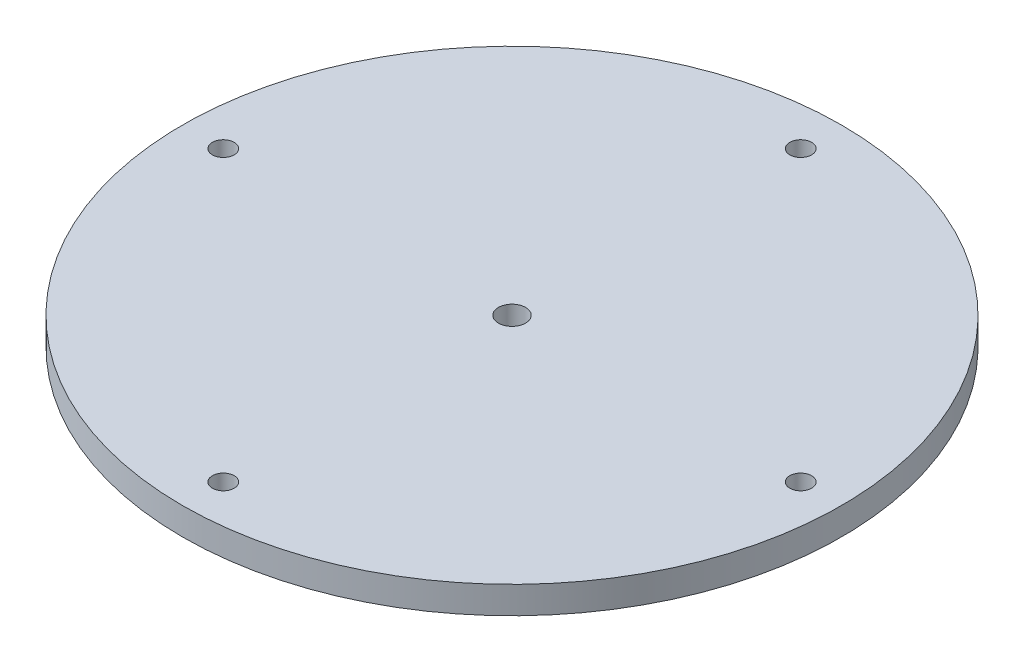
SolidWorks part; units mm, degrees
ref_plane "Front Plane" through (0, 0, 0) normal (0, 0, 1) x (1, 0, 0)
ref_plane "Top Plane" through (0, 0, 0) normal (0, 1, 0) x (1, 0, 0)
ref_plane "Right Plane" through (0, 0, 0) normal (1, 0, 0) x (0, 0, -1)
sketch "Sketch1" plane through (0, 0, 0) normal (0, 1, 0) x (1, 0, 0)
  circle A0 centre (0, 0) radius 60.5
  circle A1 centre (0, 0) radius 2.5
extrude "Boss-Extrude1" add sketch "Sketch1" along normal blind 5
sketch "Sketch2" plane through (0, 0, 0) normal (0, -1, 0) x (1, 0, 0)
  circle A0 centre (0, 53) radius 5
  circle A1 centre (53, 0) radius 5
  circle A2 centre (0, -53) radius 5
  circle A3 centre (-53, 0) radius 5
  point P12 (0, 0)
  dimension "D1" = 53
  dimension "D2" = 4
extrude "Cut-Extrude1" cut sketch "Sketch2" against normal blind 2
sketch "Sketch4" plane through (0, 2, 0) normal (0, -1, 0) x (-1, 0, 0)
  circle A0 centre (0, -53) radius 2
  circle A1 centre (-53, 0) radius 2
  circle A2 centre (0, 53) radius 2
  circle A3 centre (53, 0) radius 2
  point P12 (0, 0)
  dimension "D1" = 4
extrude "Cut-Extrude2" cut sketch "Sketch4" against normal through all
